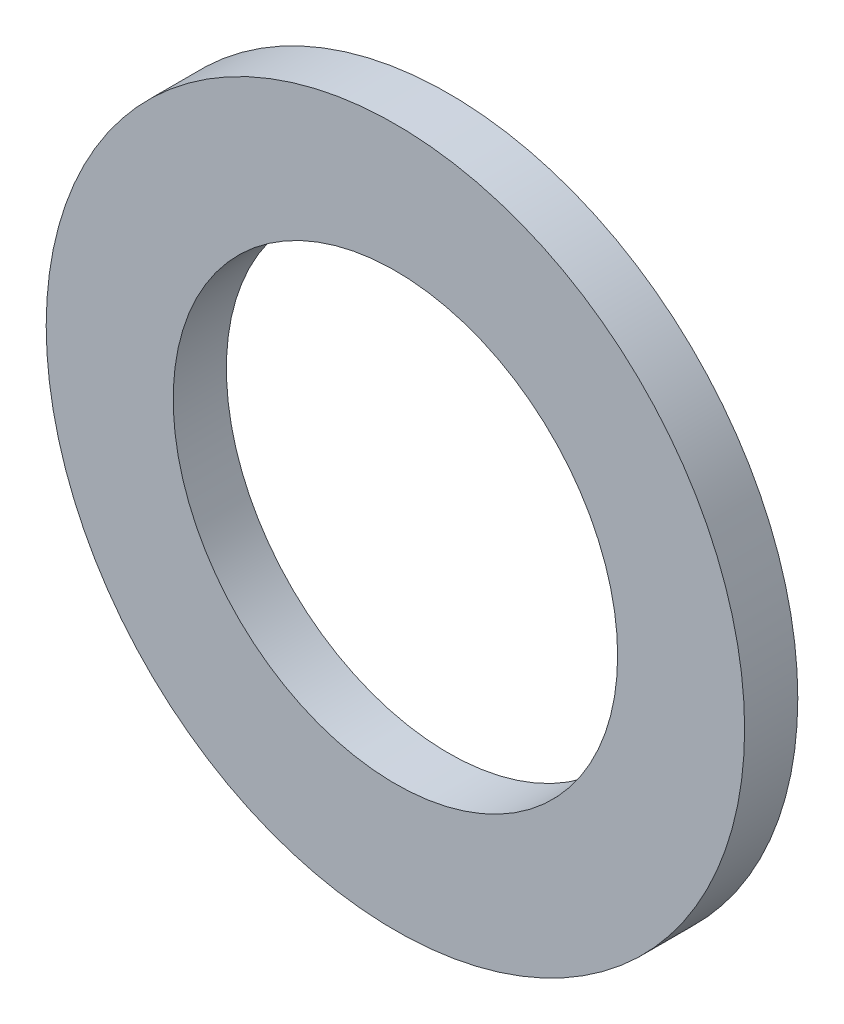
SolidWorks part; units mm, degrees
ref_plane "Ön Düzlem" through (0, 0, 0) normal (0, 0, 1) x (1, 0, 0)
ref_plane "Üst Düzlem" through (0, 0, 0) normal (0, 1, 0) x (1, 0, 0)
ref_plane "Sağ Düzlem" through (0, 0, 0) normal (1, 0, 0) x (0, 0, -1)
sketch "Çizim1" plane through (0, 0, 0) normal (0, 0, 1) x (1, 0, 0)
  circle A0 centre (0, 0) radius 14
  dimension "D1" = 28
extrude "Ekstrüzyon-İnce1" add sketch "Çizim1" along normal blind 3.35 thin
